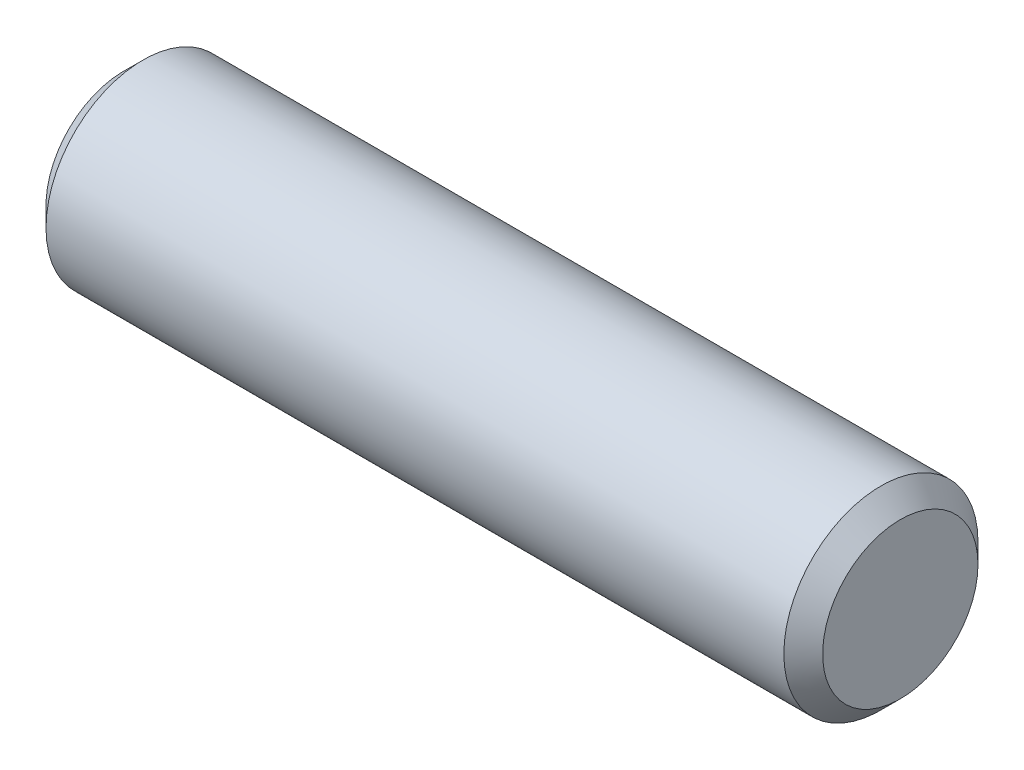
SolidWorks part; units mm, degrees
ref_plane "Front" through (0, 0, 0) normal (0, 0, 1) x (1, 0, 0)
ref_plane "Top" through (0, 0, 0) normal (0, 1, 0) x (1, 0, 0)
ref_plane "Right" through (0, 0, 0) normal (1, 0, 0) x (0, 0, -1)
sketch "Sketch1" plane through (0, 0, 0) normal (0, 0, 1) x (1, 0, 0)
  line L0 (-50.8, 0) -> (50.8, 0) construction
  line L1 (50.8, 12.7) -> (50.8, -12.7) construction
  line L2 (-50.8, 12.7) -> (-50.8, -12.7) construction
  dimension "Length" = 101.6
  dimension "Diameter" = 25.4
sketch "Sketch2" plane through (0, 0, 0) normal (1, 0, 0) x (0, 0, -1)
  circle A0 centre (0, 0) radius 12.7
extrude "Extrude1" add sketch "Sketch2" against normal up to vertex (50.8 mm away) and the other way up to vertex (50.8 mm away) up to point (-50.8, 12.7, 0) other way up to point (50.8, 12.7, 0)
chamfer "Chamfer1" distance 2.54 angle 45 2 edges at (50.8, 0, -12.7) (-50.8, 0, -12.7)
equation "\"D1@Chamfer1\" = \"Diameter@Sketch1\"*.1"
